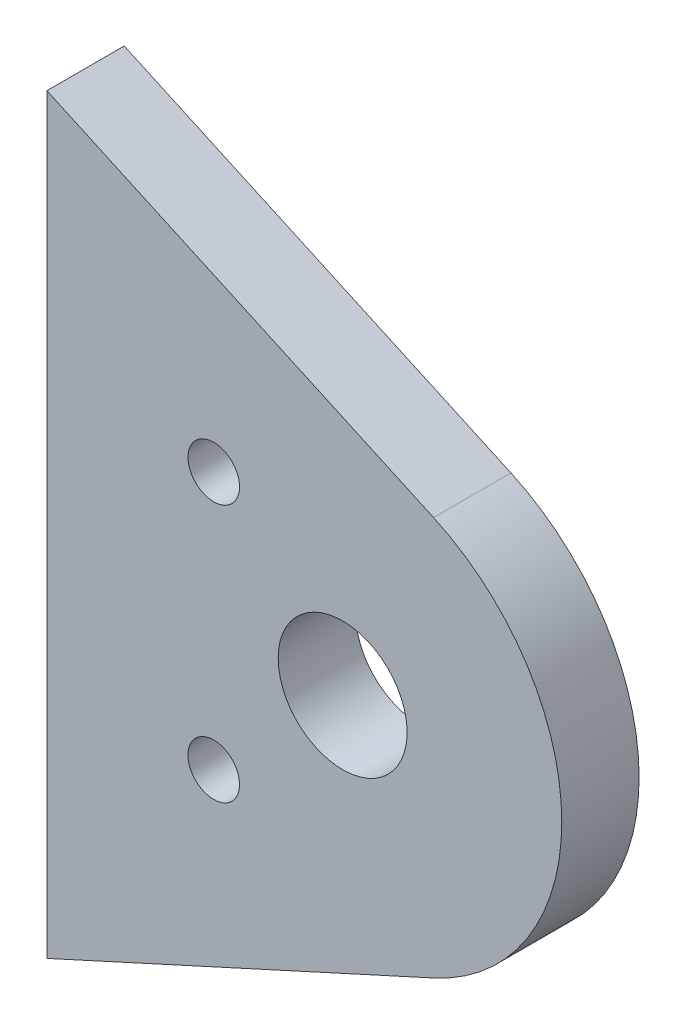
SolidWorks part; units mm, degrees
ref_plane "Face" through (0, 0, 0) normal (0, 0, 1) x (1, 0, 0)
ref_plane "Dessus" through (0, 0, 0) normal (0, 1, 0) x (1, 0, 0)
ref_plane "Droite" through (0, 0, 0) normal (1, 0, 0) x (0, 0, -1)
sketch "Esquisse1" plane through (0, 0, 0) normal (0, 0, 1) x (1, 0, 0)
  line L0 (50, 0) -> (0, 0) construction
  line L1 (12.1387, 26.6123) -> (53.5275, 7.7335)
  line L2 (-29.25, 0) -> (0, 0) construction
  line L3 (12.1388, -26.6123) -> (53.5275, -7.7335)
  line L4 (58.5, 0) -> (50, 0) construction
  circle A0 centre (0, 0) radius 19.25
  circle A1 centre (50, 0) radius 2.5
  arc A2 (12.1387, 26.6123) -> (12.1388, -26.6123) centre (0, 0) ccw
  arc A3 (53.5275, 7.7335) -> (53.5275, -7.7335) centre (50, 0) cw
  dimension "D1" = 38.5
  dimension "D2" = 5
  dimension "D4" = 10
  dimension "D5" = 6
  dimension "D3" = 50
extrude "Boss.-Extru.1" add sketch "Esquisse1" along normal blind 42
sketch "Esquisse2" plane through (5.2188, 0, 0) normal (0, 1, 0) x (1, 0, 0)
  line L0 (33.3087, -36) -> (-56.6913, -36)
  line L1 (-56.6913, -36) -> (-56.6913, -6)
  line L2 (48.3087, -21) -> (6.9199, -21) construction
  line L3 (48.3087, -42) -> (48.3087, 0) construction
  line L4 (6.9199, -42) -> (6.9199, 0) construction
  line L5 (48.3087, -42) -> (6.9199, -42) construction
  line L6 (33.3087, -36) -> (33.3087, -6)
  line L7 (33.3087, -6) -> (-56.6913, -6)
  point P13 (33.3087, -21)
  point P14 (-56.6913, -21)
  dimension "D1" = 6
  dimension "D2" = 90
  dimension "D3" = 15
extrude "Enlèv. mat.-Extru.1" cut sketch "Esquisse2" against normal through all both and the other way through all
sketch "Esquisse3" plane through (0, 0, 42) normal (0, 0, 1) x (1, 0, 0)
  line L0 (50, 0) -> (45, 0) construction
  line L1 (45, 0) -> (45, 5) construction
  line L2 (-15, 19) -> (-15, 0) construction
  line L3 (-15, 0) -> (50, 0) construction
  circle A0 centre (45, 5) radius 1
  circle A1 centre (45, -5) radius 1
  circle A2 centre (-15, 19) radius 1
  circle A3 centre (-15, -19) radius 1
  dimension "D1" = 2
  dimension "D2" = 5
  dimension "D3" = 5
  dimension "D4" = 65
  dimension "D5" = 19
extrude "Enlèv. mat.-Extru.2" cut sketch "Esquisse3" against normal up to vertex (42 mm away) up to point (53.5275, 7.7335, 0)
sketch "Esquisse4" plane through (0, 0, 0) normal (0, 1, 0) x (1, 0, 0)
  line L0 (58.5, -42) -> (58.5, 0) construction
  line L1 (-29.25, -42) -> (58.5, -42)
  line L2 (-29.25, -42) -> (-29.25, -9)
  line L3 (-29.25, -9) -> (58.5, -9)
  line L4 (58.5, -42) -> (58.5, -9)
  line L5 (53.5275, 0) -> (12.1388, 0) construction
  line L7 (-29.25, -6) -> (58.5, -6)
  line L8 (-29.25, -6) -> (-29.25, 0)
  line L9 (-29.25, 0) -> (58.5, 0)
  line L10 (58.5, -6) -> (58.5, 0)
  dimension "D1" = 9
extrude "Enlèv. mat.-Extru.3" cut sketch "Esquisse4" against normal through all both and the other way through all
